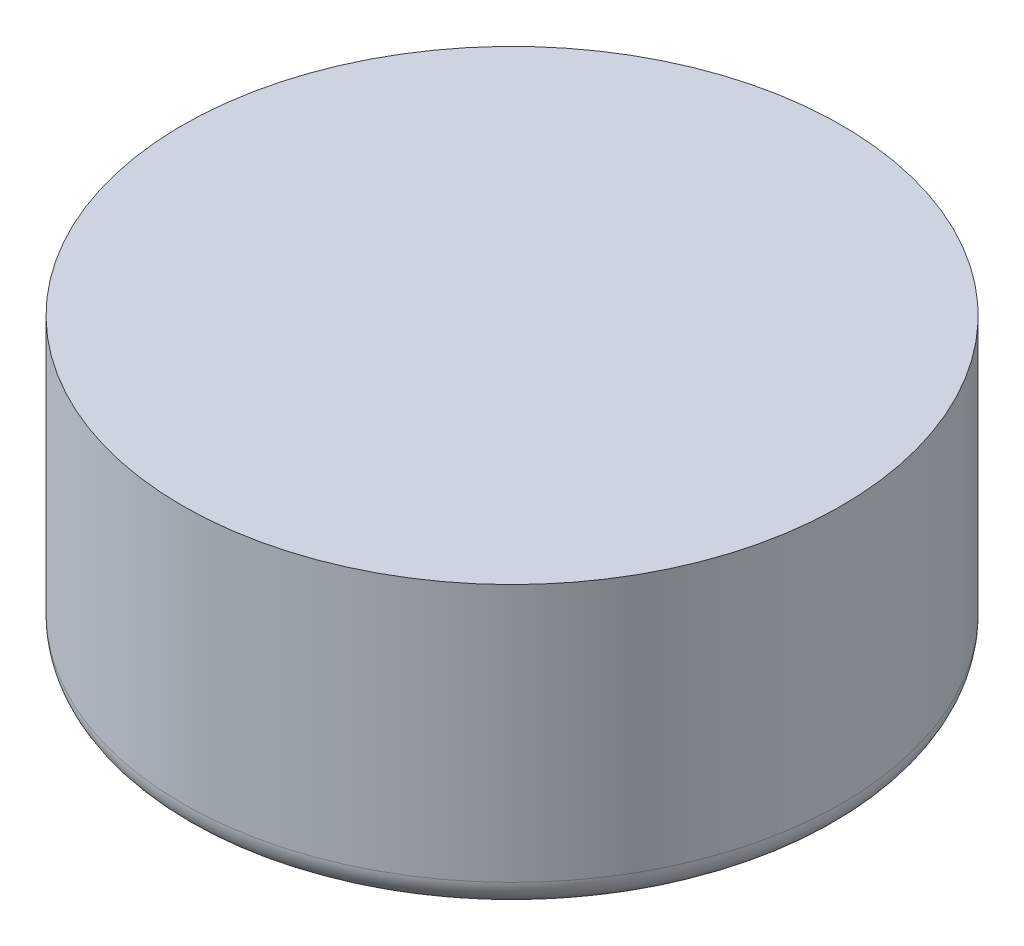
SolidWorks part; units mm, degrees
ref_plane "Front Plane" through (0, 0, 0) normal (0, 0, 1) x (1, 0, 0)
ref_plane "Top Plane" through (0, 0, 0) normal (0, 1, 0) x (1, 0, 0)
ref_plane "Right Plane" through (0, 0, 0) normal (1, 0, 0) x (0, 0, -1)
sketch "Sketch1" plane through (0, 0, 0) normal (0, 1, 0) x (1, 0, 0)
  circle A0 centre (0, 0) radius 14.605
  circle A1 centre (0, 0) radius 12.7 construction
  dimension "D1" = 25.4
  dimension "D2" = 29.21
extrude "Boss-Extrude1" add sketch "Sketch1" along normal blind 12.7
fillet "Fillet1" radius 1.27 1 edges at (0, 0, 14.605)
